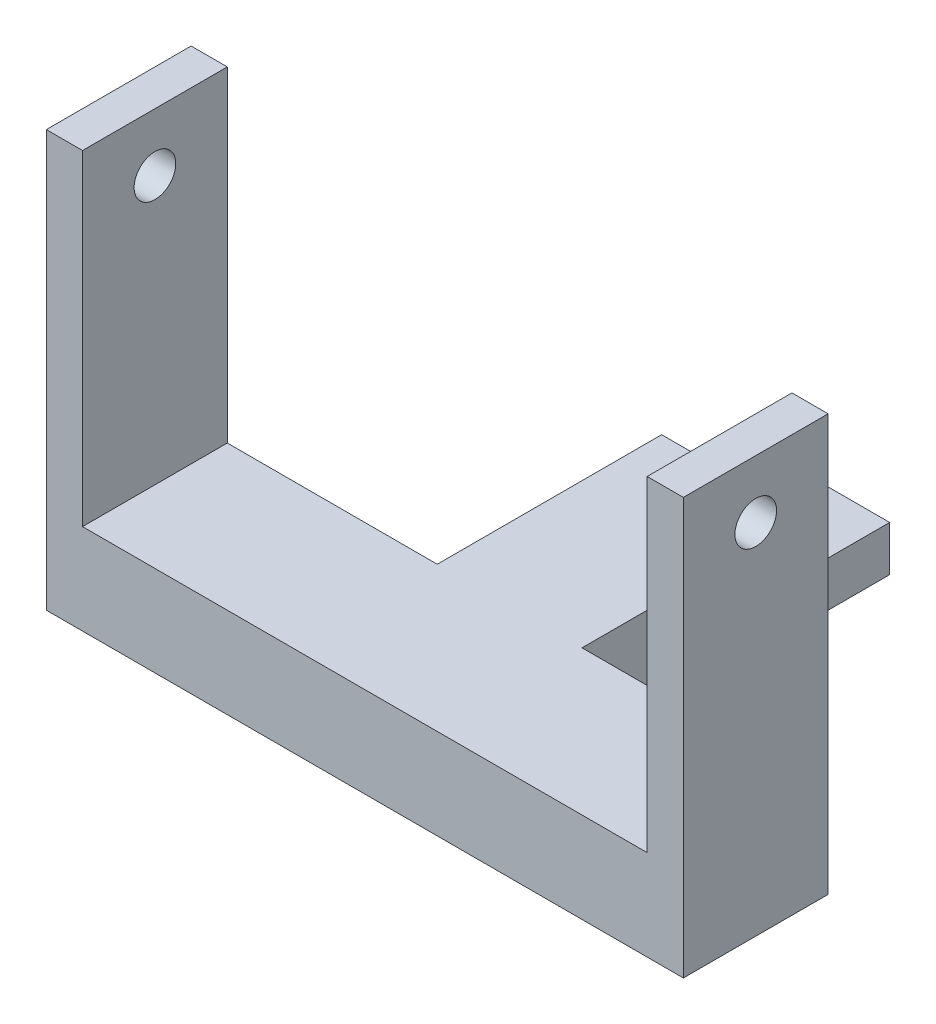
SolidWorks part; units mm, degrees
ref_plane "前视基准面" through (0, 0, 0) normal (0, 0, 1) x (1, 0, 0)
ref_plane "上视基准面" through (0, 0, 0) normal (0, 1, 0) x (1, 0, 0)
ref_plane "右视基准面" through (0, 0, 0) normal (1, 0, 0) x (0, 0, -1)
other "Configuration Table"
sketch "草图1" plane through (0, 0, 0) normal (0, 1, 0) x (1, 0, 0)
  line L1 (78, -20) -> (-78, -20)
  line L2 (78, -20) -> (78, 20)
  line L3 (78, 20) -> (-78, 20)
  line L4 (-78, -20) -> (-78, 20)
  line L5 (78, -20) -> (-78, 20) construction
  line L6 (78, 20) -> (-78, -20) construction
  point P0 (0, 0)
  dimension "D1" = 156
  dimension "D2" = 20
extrude "凸台-拉伸1" add sketch "草图1" along normal blind 20 contours L4 L3 L2 L1
sketch "草图2" plane through (-78, 0, 0) normal (-1, 0, 0) x (0, 0, 1)
  line L1 (-20, 20) -> (20, 20)
  line L2 (-20, 20) -> (-20, 0)
  line L3 (-20, 0) -> (20, 0)
  line L4 (20, 20) -> (20, 0)
extrude "凸台-拉伸2" add sketch "草图2" along normal blind 10 separate body
sketch "草图3" plane through (78, 0, 0) normal (1, 0, 0) x (0, 0, -1)
  line L1 (-20, 20) -> (20, 20)
  line L2 (-20, 20) -> (-20, 0)
  line L3 (-20, 0) -> (20, 0)
  line L4 (20, 20) -> (20, 0)
extrude "凸台-拉伸3" add sketch "草图3" along normal blind 10 separate body
sketch "草图4" plane through (0, 20, 0) normal (0, 1, 0) x (1, 0, 0)
  line L1 (-88, 20) -> (-78, 20)
  line L2 (-88, 20) -> (-88, -20)
  line L3 (-88, -20) -> (-78, -20)
  line L4 (-78, 20) -> (-78, -20)
extrude "凸台-拉伸4" add sketch "草图4" along normal blind 80
sketch "草图5" plane through (0, 20, 0) normal (0, 1, 0) x (1, 0, 0)
  line L1 (78, 20) -> (88, 20)
  line L2 (78, 20) -> (78, -20)
  line L3 (78, -20) -> (88, -20)
  line L4 (88, 20) -> (88, -20)
extrude "凸台-拉伸5" add sketch "草图5" along normal blind 80
sketch "草图6" plane through (-88, 0, 0) normal (-1, 0, 0) x (0, 0, 1)
  line L0 (0, 100) -> (0, 0) construction
  line L1 (-20, 100) -> (20, 100) construction
  line L2 (-20, 0) -> (20, 0) construction
  circle A0 centre (0, 84) radius 5.75
  dimension "D1" = 11.5
  dimension "D2" = 84
extrude "切除-拉伸1" cut sketch "草图6" against normal blind 194
sketch "草图7" plane through (0, 0, 0) normal (0, -1, 0) x (1, 0, 0)
  line L0 (-88, 20) -> (88, -20) construction
  line L1 (-88, -20) -> (88, 20) construction
  line L2 (88, 20) -> (-88, 20) construction
  line L3 (20, -20) -> (-20, -20)
  line L4 (20, -20) -> (20, 20)
  line L5 (20, 20) -> (-20, 20)
  line L6 (-20, -20) -> (-20, 20)
  line L7 (20, -20) -> (-20, 20) construction
  line L8 (20, 20) -> (-20, -20) construction
  point P8 (0, 0)
  dimension "D1" = 20
extrude "凸台-拉伸6" add sketch "草图7" along normal blind 15
sketch "草图8" plane through (0, 0, -20) normal (0, 0, -1) x (-1, 0, 0)
  line L1 (-20, -15) -> (20, -15)
  line L2 (-20, -15) -> (-20, 10)
  line L3 (-20, 10) -> (20, 10)
  line L4 (20, -15) -> (20, 10)
  dimension "D1" = 40
  dimension "D2" = 25
extrude "凸台-拉伸7" add sketch "草图8" along normal blind 85
sketch "草图9" plane through (-20, 0, 0) normal (-1, 0, 0) x (0, 0, 1)
  line L1 (-105, 10) -> (-82, 10)
  line L2 (-105, 10) -> (-105, -2.5)
  line L3 (-105, -2.5) -> (-82, -2.5)
  line L4 (-82, 10) -> (-82, -2.5)
  dimension "D1" = 23
  dimension "D2" = 12.5
extrude "切除-拉伸2" cut sketch "草图9" against normal blind 43 contours L2 L3 L4 L1
sketch "草图10" plane through (0, -2.5, 0) normal (0, 1, 0) x (1, 0, 0)
  line L0 (-20, 105) -> (20, 82) construction
  line L1 (-20, 82) -> (20, 105) construction
  circle A0 centre (0, 93.5) radius 2.1
  dimension "D1" = 4.2
extrude "切除-拉伸3" cut sketch "草图10" against normal blind 43
sketch "草图11" plane through (0, 0, 0) normal (0, -1, 0) x (1, 0, 0)
  line L1 (20, 20) -> (88, 20)
  line L2 (20, 20) -> (20, -20)
  line L3 (20, -20) -> (88, -20)
  line L4 (88, 20) -> (88, -20)
extrude "凸台-拉伸8" add sketch "草图11" along normal blind 15
sketch "草图12" plane through (0, 0, 0) normal (0, -1, 0) x (1, 0, 0)
  line L1 (-88, 20) -> (-20, 20)
  line L2 (-88, 20) -> (-88, -20)
  line L3 (-88, -20) -> (-20, -20)
  line L4 (-20, 20) -> (-20, -20)
extrude "凸台-拉伸9" add sketch "草图12" along normal blind 15
sketch "草图13" plane through (0, 20, 0) normal (0, 1, 0) x (1, 0, 0)
  line L1 (-78, 20) -> (78, 20)
  line L2 (-78, 20) -> (-78, -20)
  line L3 (-78, -20) -> (78, -20)
  line L4 (78, 20) -> (78, -20)
extrude "切除-拉伸4" cut sketch "草图13" against normal blind 10
